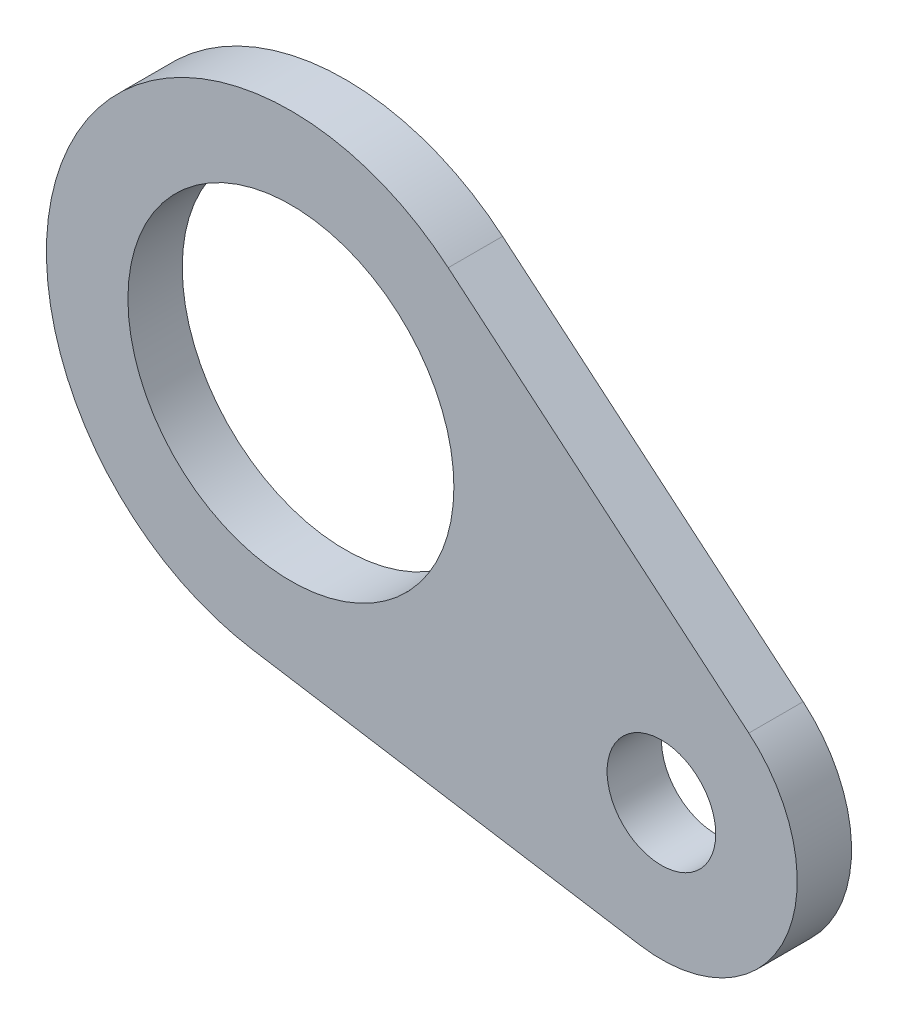
SolidWorks part; units mm, degrees
ref_plane "Front" through (0, 0, 0) normal (0, 0, 1) x (1, 0, 0)
ref_plane "Top" through (0, 0, 0) normal (0, 1, 0) x (1, 0, 0)
ref_plane "Right" through (0, 0, 0) normal (1, 0, 0) x (0, 0, -1)
sketch "Body Driving Dimensions" plane through (0, 0, 0) normal (0, 0, 1) x (1, 0, 0)
  line L0 (0, 0) -> (55.1074, -64.7161)
  line L1 (55.1074, -64.7161) -> (0, -241.3179)
  line L2 (0, -241.3179) -> (-55.1074, -64.7161)
  line L3 (-55.1074, -64.7161) -> (0, 0)
  line L4 (0, 0) -> (0, -36.971) construction
  line L5 (0, 0) -> (153.5661, 98.7013)
  line L6 (153.5661, 98.7013) -> (55.1074, -64.7161)
  line L7 (0, 0) -> (-104.5705, 47.854)
  line L8 (-104.5705, 47.854) -> (-55.1074, -64.7161)
  line L9 (153.5661, 98.7013) -> (256.2032, 164.669) construction
  line L10 (-104.5705, 47.854) -> (-215.514, 98.6245) construction
  line L11 (153.5661, 98.7013) -> (153.5661, 67.0292) construction
  line L12 (-104.5705, 47.854) -> (-104.5705, 16.182) construction
  line L13 (0, 0) -> (-98.8336, -98.8336) construction
  line L14 (0, 0) -> (98.8336, -98.8336) construction
  line L15 (-126.9179, 47.0834) -> (-118.5955, 65.2696)
  line L16 (175.7975, 101.1026) -> (164.9839, 117.9272)
  point P16 (-122.7567, 56.1765)
  point P20 (170.3907, 109.5149)
  dimension "D1" = 45
  dimension "D2" = 45
  dimension "D3" = 185
  dimension "D4" = 85
  dimension "D5" = 182.55
  dimension "D6" = 115
  dimension "D7" = 122.73
  dimension "D8" = 114.59
  dimension "D9" = 20
  dimension "D10" = 20
  dimension "D11" = 20
  dimension "D12" = 20
sketch "Sketch38" plane through (0, 0, 0) normal (0, 0, 1) x (1, 0, 0)
  line L0 (-104.5705, 47.854) -> (-215.514, 98.6245) construction
  line L1 (-108.4944, 54.4193) -> (-102.9617, 49.7676)
  line L2 (-112.1039, 46.5319) -> (-104.9669, 45.3857)
  circle A0 centre (-104.5705, 47.854) radius 1
  circle A1 centre (-111.3903, 50.975) radius 3
  circle A2 centre (-111.3903, 50.975) radius 4.5 construction
  circle A3 centre (-104.5705, 47.854) radius 2.5 construction
  arc A4 (-102.9617, 49.7676) -> (-104.9669, 45.3857) centre (-104.5705, 47.854) cw
  arc A5 (-108.4944, 54.4193) -> (-112.1039, 46.5319) centre (-111.3903, 50.975) ccw
  dimension "D1" = 2
  dimension "D2" = 6
  dimension "D3" = 9
  dimension "D4" = 5
  dimension "D5" = 7.5
extrude "Boss-Extrude13" add sketch "Sketch38" along normal blind 1 contours L1 A5 L2 A4 A0 A1
sketch "Sketch29" [suppressed] plane through (0, 0, 0) normal (0, 0, 1) x (1, 0, 0)
  line L0 (-126.9179, 47.0834) -> (-118.5955, 65.2696) construction
  line L1 (-133.7377, 50.2043) -> (-125.4153, 68.3905)
  line L2 (-120.0981, 43.9625) -> (-111.7756, 62.1487)
  arc A0 (-133.7377, 50.2043) -> (-120.0981, 43.9625) centre (-126.9179, 47.0834) ccw
  arc A1 (-111.7756, 62.1487) -> (-125.4153, 68.3905) centre (-118.5955, 65.2696) ccw
  point P4 (-122.7567, 56.1765)
  dimension "D1" = 15
extrude "Boss-Extrude14" [suppressed] add sketch "Sketch29" along normal blind 82
sketch "Sketch46" [suppressed] plane through (0, 0, 82) normal (0, 0, 1) x (1, 0, 0)
  circle A0 centre (-126.9179, 47.0834) radius 3.775
  circle A1 centre (-118.5955, 65.2696) radius 3.775
  dimension "D1" = 7.55
  dimension "D2" = 7.55
extrude "Cut-Extrude13" [suppressed] cut sketch "Sketch46" against normal blind 10
sketch "Sketch47" [suppressed] plane through (0, 0, 0) normal (0, 0, -1) x (-1, 0, 0)
  circle A0 centre (118.5955, 65.2696) radius 3.775
  circle A1 centre (126.9179, 47.0834) radius 3.775
  dimension "D1" = 7.55
  dimension "D2" = 7.55
extrude "Cut-Extrude14" [suppressed] cut sketch "Sketch47" against normal blind 10
sketch "Sketch48" [suppressed] plane through (-115.9369, 53.0556, 0) normal (0.9093, -0.4161, 0) x (0, 0, -1)
  line L0 (-82, 0) -> (0, 0) construction
  line L1 (-82, -10) -> (-82, 10) construction
  line L2 (0, 0) -> (-41, 0) construction
  line L3 (-41, 0) -> (-41, 10) construction
  line L4 (-82, 10) -> (0, 10) construction
  line L5 (-32, -10) -> (-32, 10) construction
  line L6 (-82, -10) -> (0, -10) construction
  line L7 (-34, 6) -> (-39, 6)
  line L8 (-30, -6) -> (-25, -6)
  line L9 (-30, -6) -> (-30, 6)
  line L10 (-30, 6) -> (-25, 6)
  line L11 (-25, -6) -> (-25, 6)
  line L12 (-30, -6) -> (-25, 6) construction
  line L13 (-30, 6) -> (-25, -6) construction
  line L14 (-39, -6) -> (-39, 6)
  line L15 (-34, -6) -> (-39, -6)
  line L16 (-34, -6) -> (-34, 6)
  point P13 (-27.5, 0)
  dimension "D1" = 9
  dimension "D2" = 5
  dimension "D3" = 2
  dimension "D4" = 12
extrude "Boss-Extrude15" [suppressed] add sketch "Sketch48" along normal blind 10
sketch "Sketch49" [suppressed] plane through (0, 0, 39) normal (0, 0, 1) x (1, 0, 0)
  line L0 (-104.5705, 47.854) -> (-215.514, 98.6245) construction
  line L1 (-113.4401, 58.5114) -> (-118.4336, 47.5997) construction
  circle A0 centre (-111.3903, 50.975) radius 2.5
  dimension "D1" = 5
  dimension "D2" = 5
extrude "Cut-Extrude15" [suppressed] cut sketch "Sketch49" against normal through all
fillet "Fillet14" [suppressed] radius 5
sketch "Sketch1" plane through (0, 0, 0) normal (0, 0, 1) x (1, 0, 0)
  line L0 (-55.1074, -64.7161) -> (0, -241.3179) construction
  line L1 (-47.9478, -62.4821) -> (7.1595, -239.0838)
  line L2 (-62.2669, -66.9502) -> (-7.1595, -243.552)
  circle A0 centre (-55.1074, -64.7161) radius 3.5
  circle A1 centre (0, -241.3179) radius 3.5
  arc A2 (-47.9478, -62.4821) -> (-62.2669, -66.9502) centre (-55.1074, -64.7161) ccw
  arc A3 (-7.1595, -243.552) -> (7.1595, -239.0838) centre (0, -241.3179) ccw
  point P6 (-27.5537, -153.017)
  dimension "D1" = 7
  dimension "D2" = 7.5
extrude "Tibya" [suppressed] add sketch "Sketch1" along normal blind 6
sketch "Sketch2" [suppressed] plane through (0, 0, 0) normal (0, 0, 1) x (1, 0, 0)
  line L0 (0, 0) -> (85, 0) construction
  line L1 (0, 0) -> (55.1074, -64.7161) construction
  line L2 (85.6537, 7.4715) -> (16.0331, 13.5625)
  line L4 (85.6537, -7.4715) -> (16.0331, -13.5625)
  circle A0 centre (0, 0) radius 17.5 construction
  circle A1 centre (0, 17.5) radius 1.65
  circle A2 centre (-17.5, 0) radius 1.65
  circle A3 centre (17.5, 0) radius 1.65
  circle A4 centre (0, -17.5) radius 1.65
  circle A5 centre (85, 0) radius 3.5
  circle A6 centre (85, 0) radius 7.5 construction
  circle A7 centre (0, 0) radius 21 construction
  arc A8 (85.6537, 7.4715) -> (85.6537, -7.4715) centre (85, 0) cw
  arc A9 (16.0331, 13.5625) -> (16.0331, -13.5625) centre (0, 0) ccw
  circle A10 centre (0, 0) radius 7
  dimension "D1" = 3.3
  dimension "D2" = 35
  dimension "D3" = 7
  dimension "D4" = 42
  dimension "D5" = 15
  dimension "D6" = 14
  dimension "D7" = 5
extrude "Boss-Extrude2" [suppressed] add sketch "Sketch2" along normal blind 6
fillet "Fillet1" [suppressed] radius 5
sketch "Sketch4" [suppressed] plane through (0, 0, 0) normal (1, 0, 0) x (0, 0, -1)
  line L0 (27.75, 0) -> (-27.75, 0)
  point P4 (0, 0)
  dimension "D1" = 55.5
sketch "Sketch5" [suppressed] plane through (0, 0, 0) normal (0, 1, 0) x (1, 0, 0)
  circle A0 centre (0, 0) radius 3.5
  circle A2 centre (0, 0) radius 3.25
  dimension "D1" = 7
  dimension "D2" = 0.25
extrude "Boss-Extrude3" [suppressed] add sketch "Sketch5" against normal blind 278
sketch "Sketch6" plane through (0, 0, 0) normal (0, 0, 1) x (1, 0, 0)
  line L0 (-33.3042, 78.2038) -> (-104.5705, 47.854) construction
  line L1 (-7.3776, 84.6792) -> (153.5661, 98.7013) construction
  circle A0 centre (0, 0) radius 85 construction
  circle A1 centre (0, 0) radius 182.55 construction
  circle A2 centre (0, 0) radius 115 construction
sketch "Sketch8" [suppressed] plane through (0, 0, 0) normal (0, 0, 1) x (1, 0, 0)
  line L0 (0, 0) -> (0, 150) construction
  line L3 (0, 150) -> (0, 110) construction
  line L4 (0, 0) -> (-128.3471, 58.7348) construction
  line L7 (0, 0) -> (-100.024, 45.7734) construction
  line L8 (-100.024, 45.7734) -> (-215.514, 98.6245) construction
  line L12 (40, 115) -> (-40, 115) construction
  line L13 (40, 65) -> (-40, 65) construction
  line L14 (-136.7284, 37.6613) -> (-117.8781, 78.8529)
  line L15 (-117.8781, 78.8529) -> (-63.7414, 54.0787)
  line L16 (0, 0) -> (182.2103, 117.1117) construction
  line L17 (-136.7284, 37.6613) -> (-54.9994, 0.26)
  line L18 (-50, 66.9886) -> (-50, 125)
  line L19 (-50, 125) -> (50, 125)
  line L20 (50, 125) -> (50, 66.9886)
  line L21 (186.8433, 93.1645) -> (54.4084, 8.0449)
  line L23 (149.36, 95.9979) -> (256.2032, 164.669) construction
  line L24 (186.8433, 93.1645) -> (162.3504, 131.2721)
  line L25 (162.3504, 131.2721) -> (55.4421, 62.5591)
  line L26 (171.5914, 98.3992) -> (160.7777, 115.2238) construction
  circle A0 centre (0, 0) radius 55 construction
  circle A1 centre (0, 0) radius 177.55 construction
  circle A2 centre (0, 0) radius 45
  circle A4 centre (-40, 115) radius 2.65
  circle A5 centre (0, 0) radius 110 construction
  circle A6 centre (40, 115) radius 2.65
  circle A7 centre (0, 115) radius 2.65
  circle A8 centre (40, 65) radius 2.65
  circle A9 centre (0, 65) radius 2.65
  circle A10 centre (-40, 65) radius 2.65
  circle A11 centre (0, 0) radius 83.5911 construction
  arc A12 (-63.7414, 54.0787) -> (-50, 66.9886) centre (0, 0) cw
  arc A13 (-54.9994, 0.26) -> (54.4084, 8.0449) centre (0, 0) ccw
  arc A14 (50, 66.9886) -> (55.4421, 62.5591) centre (0, 0) cw
  point P12 (0, 177.55)
  point P17 (-127.3032, 58.2571)
  point P26 (0, 115)
  point P37 (0, 65)
  point P50 (174.5968, 112.2183)
  dimension "D2" = 110
  dimension "D3" = 90
  dimension "D10" = 5.3
  dimension "D16" = 40
  dimension "D4" = 65
  dimension "D5" = 45.3
  dimension "D6" = 10
  dimension "D7" = 45.3
  dimension "D8" = 10
  dimension "D9" = 10
  dimension "D11" = 80
  dimension "D12" = 50
  dimension "D13" = 40
  dimension "D14" = 10
  dimension "D15" = 10
extrude "Boss-Extrude12" [suppressed] add sketch "Sketch8" along normal blind 6 contours A14 L20 L19 L18 A12 L15 L14 L17 A13 L21 L24 L25 A10 A9 A8 A7 A6 A4 A2
hole_wizard "M5 Clearance Hole3" [suppressed] positions "Sketch39" profile "Sketch40" hole size "M5" standard "ANSI Metric"
sketch "Sketch39" [suppressed] plane through (0, 0, 6) normal (0, 0, 1) x (1, 0, 0)
  point P0 (-114.0489, 63.189)
  point P3 (-122.3714, 45.0028)
  point P6 (160.7777, 115.2238)
  point P9 (171.5914, 98.3992)
sketch "Sketch40" [suppressed] plane through (-114.0489, 63.189, 6) normal (1, 0, 0) x (0, -1, 0)
  line L0 (0, 0) -> (0, 6)
  line L1 (0, 6) -> (2.75, 6)
  line L2 (2.75, 6) -> (2.75, 0.025)
  line L3 (2.75, 0.025) -> (2.775, 0)
  line L5 (2.775, 0) -> (0, 0)
  line L6 (-2.75, 0.025) -> (-2.775, 0) construction
  line L11 (0, -6.35) -> (0, 107.95) construction
  dimension "Thru Hole Dia." = 5.5
  dimension "Thru Hole Depth" = 6
  dimension "Near C'Sink Dia." = 5.55
  dimension "Near C'Sink Angle" = 90
sketch "Sketch41" [suppressed] plane through (0, 0, 6) normal (0, 0, 1) x (1, 0, 0)
  line L0 (0, -45) -> (0, 45) construction
  line L1 (0, 0) -> (35.3553, 35.3553) construction
  line L2 (0, 0) -> (35.3553, -35.3553) construction
  circle A0 centre (0, 0) radius 50 construction
  circle A1 centre (0, 0) radius 45 construction
  point P10 (-35.3553, -35.3553)
  point P11 (35.3553, -35.3553)
  point P12 (35.3553, 35.3553)
  point P13 (-35.3553, 35.3553)
  dimension "D1" = 100
  dimension "D2" = 45
  dimension "D3" = 45
hole_wizard "M3 Clearance Hole2" [suppressed] positions "Sketch42" profile "Sketch43" hole size "M3" standard "ANSI Metric"
sketch "Sketch42" [suppressed] plane through (0, 0, 6) normal (0, 0, 1) x (1, 0, 0)
  point P0 (-35.3553, 35.3553)
  point P3 (35.3553, 35.3553)
  point P6 (35.3553, -35.3553)
  point P9 (-35.3553, -35.3553)
sketch "Sketch43" [suppressed] plane through (-35.3553, 35.3553, 6) normal (1, 0, 0) x (0, -1, 0)
  line L0 (0, 0) -> (0, 6)
  line L1 (0, 6) -> (1.7, 6)
  line L2 (1.7, 6) -> (1.7, 0.025)
  line L3 (1.7, 0.025) -> (1.725, 0)
  line L5 (1.725, 0) -> (0, 0)
  line L6 (-1.7, 0.025) -> (-1.725, 0) construction
  line L11 (0, -6.35) -> (0, 107.95) construction
  dimension "Thru Hole Dia." = 3.4
  dimension "Thru Hole Depth" = 6
  dimension "Near C'Sink Dia." = 3.45
  dimension "Near C'Sink Angle" = 90
sketch "Sketch45" [suppressed] plane through (0, 0, 6) normal (0, 0, 1) x (1, 0, 0)
  line L0 (-60.6547, 11.646) -> (-48.4623, 38.2887)
  line L1 (-60.6547, 11.646) -> (-117.0319, 37.4455)
  line L2 (-48.4623, 38.2887) -> (-104.8395, 64.0883)
  line L3 (-117.0319, 37.4455) -> (-104.8395, 64.0883)
  line L4 (-60.6547, 11.646) -> (-104.8395, 64.0883) construction
  line L5 (-48.4623, 38.2887) -> (-117.0319, 37.4455) construction
  line L6 (-117.8781, 78.8529) -> (-63.7414, 54.0787) construction
  line L7 (-136.7284, 37.6613) -> (-54.9994, 0.26) construction
  line L8 (0, 0) -> (-100.024, 45.7734) construction
  line L9 (-122.3714, 45.0028) -> (-114.0489, 63.189) construction
  line L10 (58.3946, 20.1169) -> (42.5527, 44.7648)
  line L11 (58.3946, 20.1169) -> (167.3757, 90.1621)
  line L12 (42.5527, 44.7648) -> (151.5338, 114.81)
  line L13 (167.3757, 90.1621) -> (151.5338, 114.81)
  line L14 (58.3946, 20.1169) -> (151.5338, 114.81) construction
  line L15 (42.5527, 44.7648) -> (167.3757, 90.1621) construction
  line L16 (0, 0) -> (149.36, 95.9979) construction
  line L17 (171.5914, 98.3992) -> (160.7777, 115.2238) construction
  line L18 (162.3504, 131.2721) -> (55.4421, 62.5591) construction
  line L19 (186.8433, 93.1645) -> (54.4084, 8.0449) construction
  point P1 (-82.7471, 37.8671)
  point P14 (-54.5585, 24.9673)
  point P16 (104.9642, 67.4635)
  dimension "D1" = 8
  dimension "D2" = 8
  dimension "D3" = 60
  dimension "D4" = 8
  dimension "D5" = 8
  dimension "D6" = 8
  dimension "D7" = 60
extrude "Cut-Extrude12" [suppressed] cut sketch "Sketch45" against normal through all
fillet "Fillet12" [suppressed] radius 5
fillet "Fillet13" [suppressed] radius 5
sketch "Sketch17" [suppressed] plane through (0, 0, 0) normal (0, 0, 1) x (1, 0, 0)
  line L0 (0, 0) -> (-45, 0) construction
  line L1 (0, 0) -> (0, 45) construction
  line L2 (0, 0) -> (-35.3553, 35.3553) construction
  line L3 (0, 0) -> (0, 170) construction
  line L4 (54, 170) -> (-54, 170)
  line L5 (-54, 170) -> (-54, 0)
  line L6 (54, 0) -> (54, 170)
  line L7 (45, 162.5) -> (-45, 162.5) construction
  line L8 (45, 112.5) -> (-45, 112.5) construction
  circle A0 centre (0, 0) radius 45
  circle A1 centre (-35.3553, 35.3553) radius 1.65
  circle A2 centre (35.3553, 35.3553) radius 1.65
  circle A3 centre (35.3553, -35.3553) radius 1.65
  circle A4 centre (-35.3553, -35.3553) radius 1.65
  circle A5 centre (0, 0) radius 54 construction
  circle A6 centre (0, 162.5) radius 2.65
  arc A7 (-54, 0) -> (54, 0) centre (0, 0) ccw
  circle A8 centre (-45, 162.5) radius 2.65
  circle A9 centre (45, 162.5) radius 2.65
  circle A10 centre (-45, 112.5) radius 2.65
  circle A11 centre (-35.3553, 35.3553) radius 4 construction
  circle A12 centre (0, 112.5) radius 2.65
  circle A13 centre (45, 112.5) radius 2.65
  point P16 (0, 0)
  point P19 (0, 170)
  point P25 (0, 162.5)
  point P33 (0, 112.5)
  dimension "D1" = 90
  dimension "D4" = 3.3
  dimension "D6" = 170
  dimension "D9" = 5.3
  dimension "D11" = 8
  dimension "D7" = 50
  dimension "D2" = 45
  dimension "D3" = 50
  dimension "D8" = 90
  dimension "D10" = 7.5
  dimension "D5" = 4
extrude "Simple Side Plate" [suppressed] add sketch "Sketch17" along normal blind 6
fillet "Fillet7" [suppressed] radius 2.5
sketch "Sketch44" [suppressed] plane through (0, 0, 6) normal (0, 0, 1) x (1, 0, 0)
  line L0 (-65.2013, 13.7266) -> (-53.0089, 40.3693)
  line L1 (-65.2013, 13.7266) -> (-115.2132, 36.6133)
  line L2 (-53.0089, 40.3693) -> (-103.0209, 63.256)
  line L3 (-115.2132, 36.6133) -> (-103.0209, 63.256)
  line L4 (-65.2013, 13.7266) -> (-103.0209, 63.256) construction
  line L5 (-53.0089, 40.3693) -> (-115.2132, 36.6133) construction
  line L6 (0, 0) -> (-100.024, 45.7734) construction
  line L7 (-117.8781, 78.8529) -> (-63.7414, 54.0787) construction
  line L8 (77.023, 48.4736) -> (68.633, 61.5274)
  line L13 (77.023, 48.4736) -> (135.2836, 85.9194)
  line L14 (68.633, 61.5274) -> (126.8936, 98.9731)
  line L17 (135.2836, 85.9194) -> (126.8936, 98.9731)
  line L18 (77.023, 48.4736) -> (126.8936, 98.9731) construction
  line L19 (68.633, 61.5274) -> (135.2836, 85.9194) construction
  line L20 (0, 0) -> (149.36, 95.9979) construction
  line L21 (162.3504, 131.2721) -> (55.4421, 62.5591) construction
  circle A0 centre (-122.3714, 45.0028) radius 2.775 construction
  point P1 (-84.1111, 38.4913)
  point P12 (101.9583, 73.7234)
  dimension "D1" = 10
  dimension "D2" = 8
  dimension "D3" = 57.5
  dimension "D4" = 8
extrude "Cut-Extrude11" [suppressed] cut sketch "Sketch44" against normal blind 81
equation "\"l2\"= 185"
equation "\"D3@Body Driving Dimensions\" = \"l2\""
equation "\"l1\"= 85"
equation "\"D4@Body Driving Dimensions\" = \"l1\""
equation "\"s1r\"= 2.14212rad"
equation "\"s2r\"= - 2rad"
equation "\"offset\" = 15mm"
equation "\"s1_len\"= 0.08255m"
equation "\"s2_len\"= 0.015m"
equation "\"s1_anchor_dist\"= \"offset\" + \"l1\" + \"s1_len\""
equation "\"s2_anchor_dist\"= \"offset\" + \"l1\" + \"s2_len\"'this was: = \"offset\" + \"l1\" + \"s2_len\""
equation "\"D5@Body Driving Dimensions\" = \"s1_anchor_dist\""
equation "\"D6@Body Driving Dimensions\" = \"s2_anchor_dist\""
equation "\"D7@Body Driving Dimensions\" = \"s1r\""
equation "\"D8@Body Driving Dimensions\" =  - \"s2r\""
equation "\"carbon_fiber_plate_thickness\"=6"
equation "\"D1@Tibya\" = \"carbon_fiber_plate_thickness\""
equation "\"D1@Boss-Extrude2\"=\"carbon_fiber_plate_thickness\""
equation "\"motor_to_motor_spacing\"=55.5"
equation "\"D1@Sketch4\"=\"motor_to_motor_spacing\""
equation "\"D1@Boss-Extrude3\"=\"l1\"+\"l2\" + 8"
equation "\"D1\" = \"motor_to_motor_spacing\" + 30mm"
equation "\"D1@Boss-Extrude12\"=\"carbon_fiber_plate_thickness\""
equation "\"D3@Sketch44\"=\"s2_anchor_dist\"/2"
